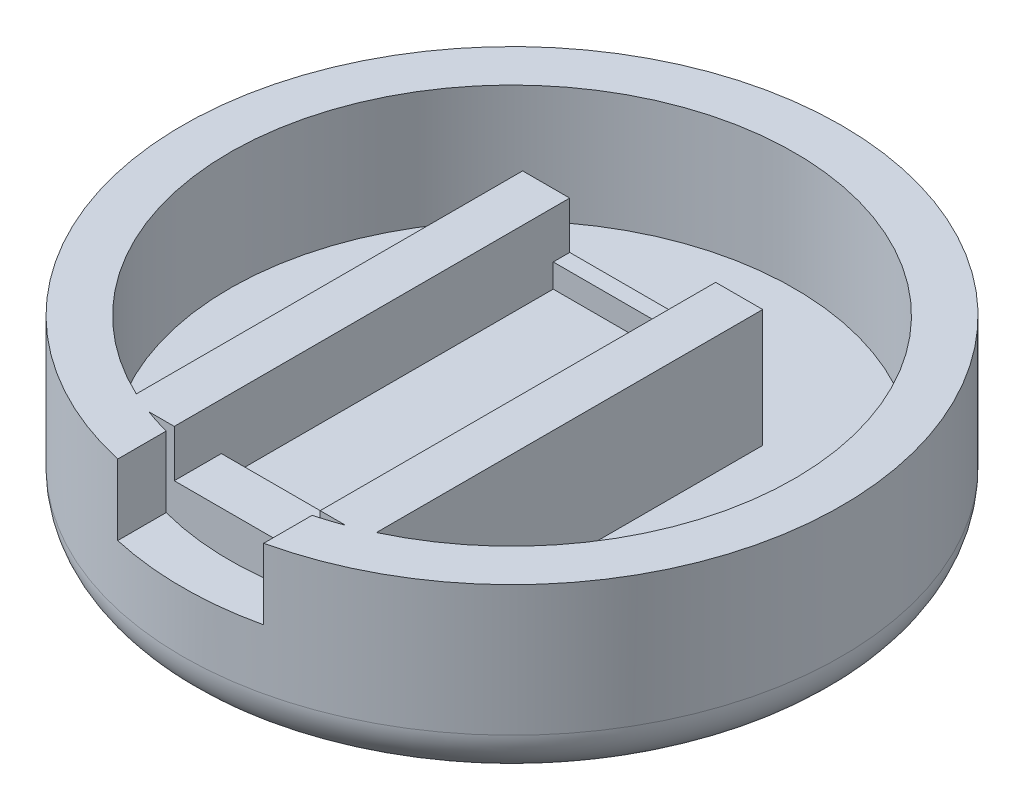
SolidWorks part; units mm, degrees
ref_plane "Front Plane" through (0, 0, 0) normal (0, 0, 1) x (1, 0, 0)
ref_plane "Top Plane" through (0, 0, 0) normal (0, 1, 0) x (1, 0, 0)
ref_plane "Right Plane" through (0, 0, 0) normal (1, 0, 0) x (0, 0, -1)
sketch "Sketch1" plane through (0, 0, 0) normal (0, 1, 0) x (1, 0, 0)
  line L8 (-32.7271, 1.6281) -> (-32.7271, -12.4719)
  line L9 (-32.7271, -12.4719) -> (-26.5271, -12.4719)
  line L10 (-26.5271, -12.4719) -> (-26.5271, 1.6281)
  line L11 (-26.5271, 1.6281) -> (-32.7271, 1.6281)
  line L12 (-34.7271, 2.3281) -> (-24.5271, 2.3281)
  line L13 (-24.5271, 2.3281) -> (-24.5271, -14.4719)
  line L14 (-24.5271, -14.4719) -> (-34.7271, -14.4719)
  line L15 (-34.7271, -14.4719) -> (-34.7271, 2.3281)
  dimension "D1" = 2
  dimension "D2" = 2
  dimension "D3" = 2
  dimension "D4" = 0.7
  dimension "D5" = 14.1
  dimension "D6" = 6.2
extrude "Boss-Extrude1" add sketch "Sketch1" along normal blind 3
sketch "Sketch2" plane through (0, 0, 14.4719) normal (0, 0, 1) x (1, 0, 0)
  line L5 (-26.5271, 3) -> (-26.5271, 0) construction
  line L6 (-32.7271, 3) -> (-26.5271, 3)
  line L7 (-32.7271, 3) -> (-32.7271, 1)
  line L8 (-32.7271, 1) -> (-26.5271, 1)
  line L9 (-26.5271, 3) -> (-26.5271, 1)
  line L10 (-34.7271, 0) -> (-24.5271, 0) construction
  dimension "D1" = 1
extrude "Cut-Extrude1" cut sketch "Sketch2" against normal blind 25.4
sketch "Sketch3" plane through (0, 0, 0) normal (0, -1, 0) x (1, 0, 0)
  line L1 (-34.7271, 14.4719) -> (-24.5271, 14.4719)
  line L2 (-34.7271, 14.4719) -> (-34.7271, -2.3281)
  line L3 (-34.7271, -2.3281) -> (-24.5271, -2.3281)
  line L4 (-24.5271, 14.4719) -> (-24.5271, -2.3281)
extrude "Boss-Extrude2" add sketch "Sketch3" along normal blind 2
sketch "Sketch4" plane through (0, -2, 0) normal (0, -1, 0) x (1, 0, 0)
  line L0 (-29.6271, 14.4719) -> (-29.6271, -13.9821) construction
  line L1 (-32.7271, 14.4719) -> (-26.5271, 14.4719) construction
  line L2 (-32.7271, 14.4719) -> (-32.7271, -8.0281) construction
  line L3 (-32.7271, -8.0281) -> (-26.5271, -8.0281) construction
  line L4 (-26.5271, 14.4719) -> (-26.5271, -8.0281) construction
  circle A0 centre (-29.6271, 3.2222) radius 12
  circle A1 centre (-29.6271, 3.2222) radius 14
  dimension "D3" = 24
  dimension "D1" = 22.5
  dimension "D2" = 11.2497
  dimension "D4" = 2
extrude "Boss-Extrude4" add sketch "Sketch4" against normal up to surface (5 mm away) up to face at (-33.7271, 3, 6.0719)
sketch "Sketch5" plane through (0, -2, 0) normal (0, -1, 0) x (1, 0, 0)
  circle A0 centre (-29.6271, 3.2222) radius 14
extrude "Boss-Extrude5" add sketch "Sketch5" along normal blind 2.54
sketch "Sketch6" plane through (0, 0, 14.4719) normal (0, 0, 1) x (1, 0, 0)
  line L1 (-32.7271, 3) -> (-26.5271, 3)
  line L2 (-32.7271, 3) -> (-32.7271, 0)
  line L3 (-32.7271, 0) -> (-26.5271, 0)
  line L4 (-26.5271, 3) -> (-26.5271, 0)
extrude "Cut-Extrude2" cut sketch "Sketch6" along normal blind 7.62
fillet "Fillet1" radius 2 1 edges at (-29.6271, -4.54, -10.7778)
